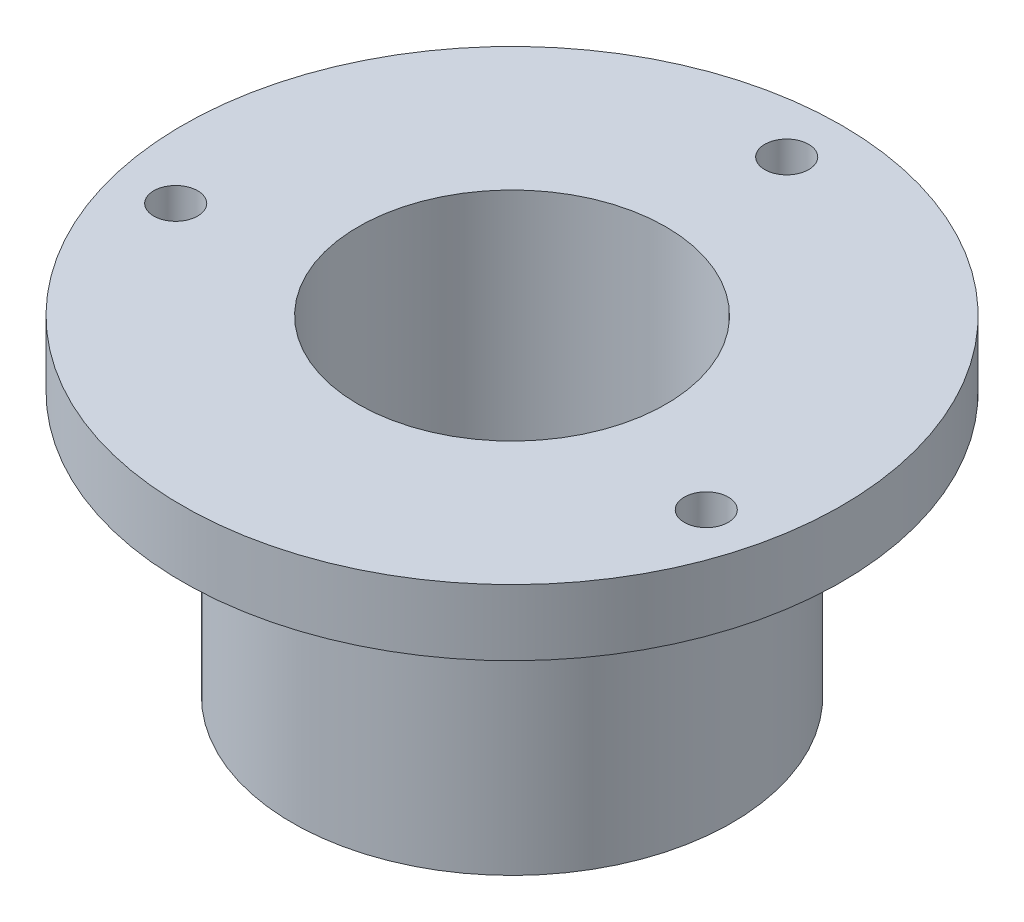
SolidWorks part; units mm, degrees
ref_plane "Front Plane" through (0, 0, 0) normal (0, 0, 1) x (1, 0, 0)
ref_plane "Top Plane" through (0, 0, 0) normal (0, 1, 0) x (1, 0, 0)
ref_plane "Right Plane" through (0, 0, 0) normal (1, 0, 0) x (0, 0, -1)
sketch "Sketch1" plane through (0, 0, 0) normal (0, 0, 1) x (1, 0, 0)
  line L0 (0, 0) -> (0, 15) construction
  line L1 (10, 0) -> (10, 12)
  line L2 (10, 12) -> (15, 12)
  line L3 (15, 12) -> (15, 15)
  line L4 (15, 15) -> (7, 15)
  line L5 (7, 15) -> (7, 0)
  line L6 (7, 0) -> (10, 0)
  line L7 (0, 0) -> (7, 0) construction
  point P4 (0, 0)
  dimension "D1" = 15
  dimension "D2" = 15
  dimension "D3" = 7
  dimension "D4" = 3
revolve "Revolve1" add sketch "Sketch1" angle 360 about L0
sketch "Sketch2" plane through (0, 15, 0) normal (0, 1, 0) x (1, 0, 0)
  line L0 (0, 0) -> (0, 12.5) construction
  line L1 (0, 0) -> (12.0741, -3.2352) construction
  line L2 (0, 0) -> (-12.0741, -3.2352) construction
  circle A0 centre (0, 0) radius 12.5 construction
  circle A1 centre (0, 12.5) radius 1
  circle A2 centre (0, 0) radius 12.5 construction
  circle A4 centre (0, 0) radius 12.5 construction
  circle A6 centre (10.8253, -6.25) radius 1 [skipped]
  circle A7 centre (-10.8253, -6.25) radius 1 [skipped]
  circle A8 centre (0, 0) radius 12.5 construction
  circle A10 centre (0, 0) radius 12.5 construction
  circle A12 centre (12.0741, -3.2352) radius 1 [skipped]
  circle A13 centre (-6.25, -10.8253) radius 1 [skipped]
  circle A14 centre (-12.0741, -3.2352) radius 1
  circle A15 centre (12.0741, -3.2352) radius 1
  circle A17 centre (0, 0) radius 12.5 construction
  circle A19 centre (0, 0) radius 12.5 construction
  dimension "D1" = 25
  dimension "D2" = 2
  dimension "D5" = 105
  dimension "D6" = 105
  dimension "D3" = 3
  dimension "D4" = 3
  dimension "D8" = 3
extrude "Cut-Extrude1" cut sketch "Sketch2" against normal through all
sketch "Sketch3" plane through (0, 0, 0) normal (0, -1, 0) x (1, 0, 0)
  circle A0 centre (0, 0) radius 8.5 construction
  circle A1 centre (0, 0) radius 8.5 construction
  circle A2 centre (0, 0) radius 8.5 construction
  circle A3 centre (0, 8.5) radius 0.8
  circle A4 centre (0, 0) radius 8.5 construction
  circle A5 centre (7.3612, -4.25) radius 0.8
  circle A6 centre (0, 0) radius 8.5 construction
  circle A7 centre (-7.3612, -4.25) radius 0.8
  point P3 (0, 8.5)
  point P5 (7.3612, -4.25)
  point P8 (-7.3612, -4.25)
  point P14 (7.3612, -4.25)
  point P18 (-7.3612, -4.25)
  dimension "D1" = 17
  dimension "D3" = 1.6
  dimension "D2" = 3
extrude "Cut-Extrude2" cut sketch "Sketch3" against normal blind 2.5
